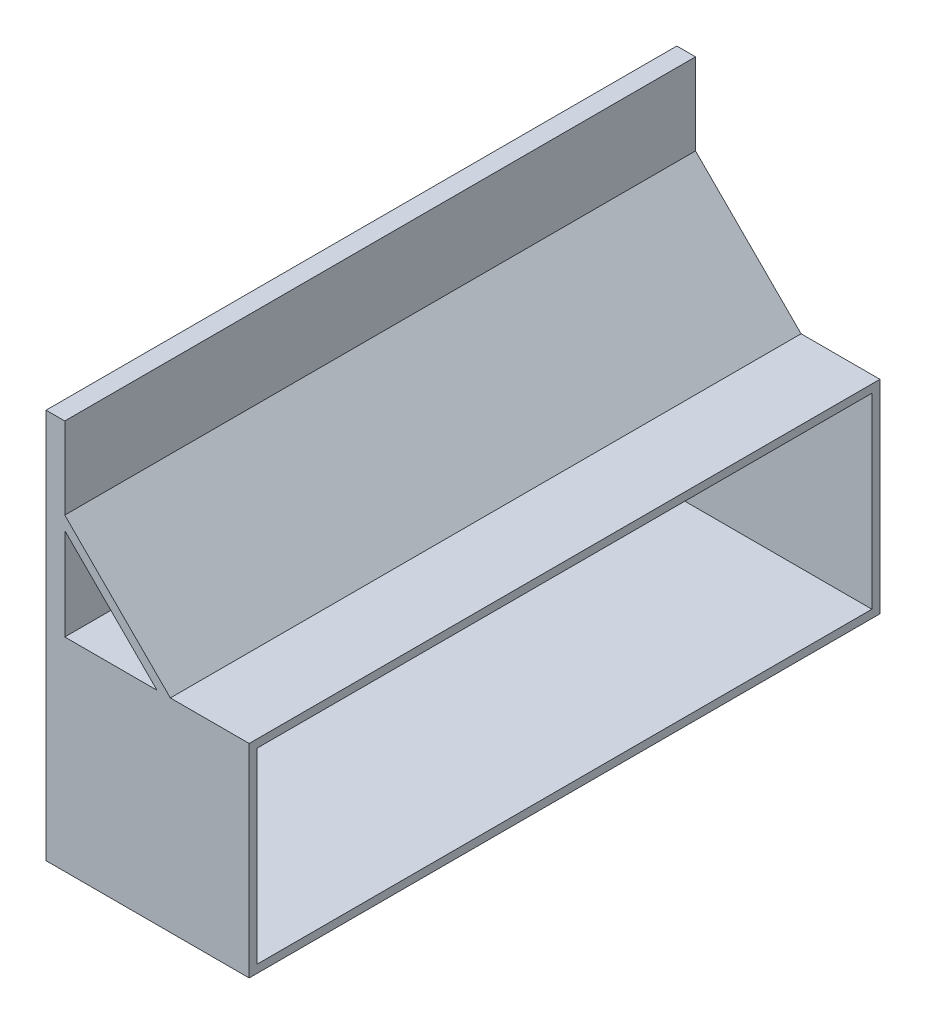
SolidWorks part; units mm, degrees
ref_plane "前基準面" through (0, 0, 0) normal (0, 0, 1) x (1, 0, 0)
ref_plane "上基準面" through (0, 0, 0) normal (0, 1, 0) x (1, 0, 0)
ref_plane "右基準面" through (0, 0, 0) normal (1, 0, 0) x (0, 0, -1)
sketch "草圖1" plane through (0, 0, 0) normal (0, 0, 1) x (1, 0, 0)
  line L1 (-46.8916, 29.1084) -> (29.1084, 29.1084)
  line L2 (-46.8916, 29.1084) -> (-46.8916, -46.8916)
  line L3 (-46.8916, -46.8916) -> (29.1084, -46.8916)
  line L4 (29.1084, 29.1084) -> (29.1084, -46.8916)
  dimension "D1" = 76
  dimension "D2" = 76
extrude "填料-伸長1" add sketch "草圖1" along normal blind 236
sketch "草圖3" plane through (-46.8916, 0, 0) normal (-1, 0, 0) x (0, 0, 1)
  line L2 (233, 26.1084) -> (3, 26.1084)
  line L3 (233, 26.1084) -> (233, -43.8916)
  line L4 (233, -43.8916) -> (3, -43.8916)
  line L5 (3, 26.1084) -> (3, -43.8916)
  line L7 (236, 29.1084) -> (0, 29.1084) construction
  line L8 (236, -46.8916) -> (0, -46.8916) construction
  line L9 (0, 29.1084) -> (0, -46.8916) construction
  line L10 (236, 29.1084) -> (236, -46.8916) construction
  dimension "D1" = 230
  dimension "D2" = 70
  dimension "D3" = 3
  dimension "D4" = 3
  dimension "D5" = 3
  dimension "D6" = 3
extrude "除料-伸長1" cut sketch "草圖3" against normal blind 130.0858 contours L3 L2 L5 L4
sketch "草圖4" plane through (0, 29.1084, 0) normal (0, 1, 0) x (1, 0, 0)
  line L0 (29.1084, 0) -> (-46.8916, 0) construction
  line L1 (-46.8916, 0) -> (-39.8916, 0)
  line L2 (-46.8916, 0) -> (-46.8916, -236)
  line L3 (-46.8916, -236) -> (-39.8916, -236)
  line L4 (-39.8916, 0) -> (-39.8916, -236)
  line L5 (-46.8916, -236) -> (-46.8916, 0) construction
  line L6 (29.1084, -236) -> (-46.8916, -236) construction
  dimension "D1" = 7
extrude "填料-伸長2" add sketch "草圖4" along normal blind 70
sketch "草圖5" plane through (0, 0, 236) normal (0, 0, 1) x (1, 0, 0)
  line L1 (-39.8916, 63.6084) -> (-5.3916, 29.1084)
  line L2 (-39.8916, 99.1084) -> (-39.8916, 29.1084) construction
  line L3 (29.1084, 29.1084) -> (-39.8916, 29.1084) construction
  line L4 (-5.3916, 29.1084) -> (-0.3916, 29.1084)
  line L5 (-0.3916, 29.1084) -> (-39.8916, 68.6084)
  line L6 (-39.8916, 68.6084) -> (-39.8916, 63.6084)
  dimension "D1" = 5
  dimension "D2" = 5
  dimension "D3" = 45
extrude "填料-伸長5" add sketch "草圖5" against normal blind 236
